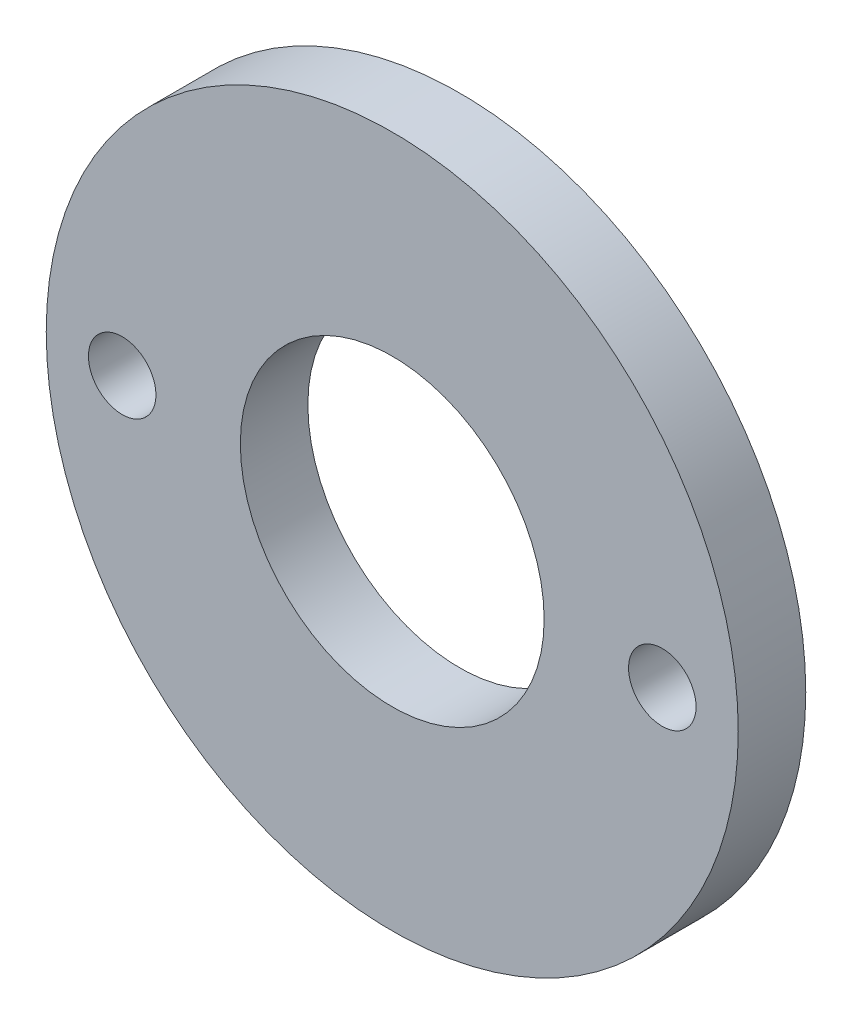
SolidWorks part; units mm, degrees
material "Thornel Mat VMA"
ref_plane "前视基准面" through (0, 0, 0) normal (0, 0, 1) x (1, 0, 0)
ref_plane "上视基准面" through (0, 0, 0) normal (0, 1, 0) x (1, 0, 0)
ref_plane "右视基准面" through (0, 0, 0) normal (1, 0, 0) x (0, 0, -1)
sketch "草图1" plane through (0, 0, 0) normal (0, 0, 1) x (1, 0, 0)
  circle A0 centre (0, 0) radius 4.5
  circle A1 centre (0, 0) radius 10.25
  circle A2 centre (0, 0) radius 8 construction
  circle A3 centre (-8, 0) radius 1
  circle A4 centre (8, 0) radius 1
  dimension "D1" = 9
  dimension "D2" = 20.5
  dimension "D3" = 16
  dimension "D4" = 2
  dimension "D5" = 2
extrude "凸台-拉伸1" add sketch "草图1" along normal blind 2
